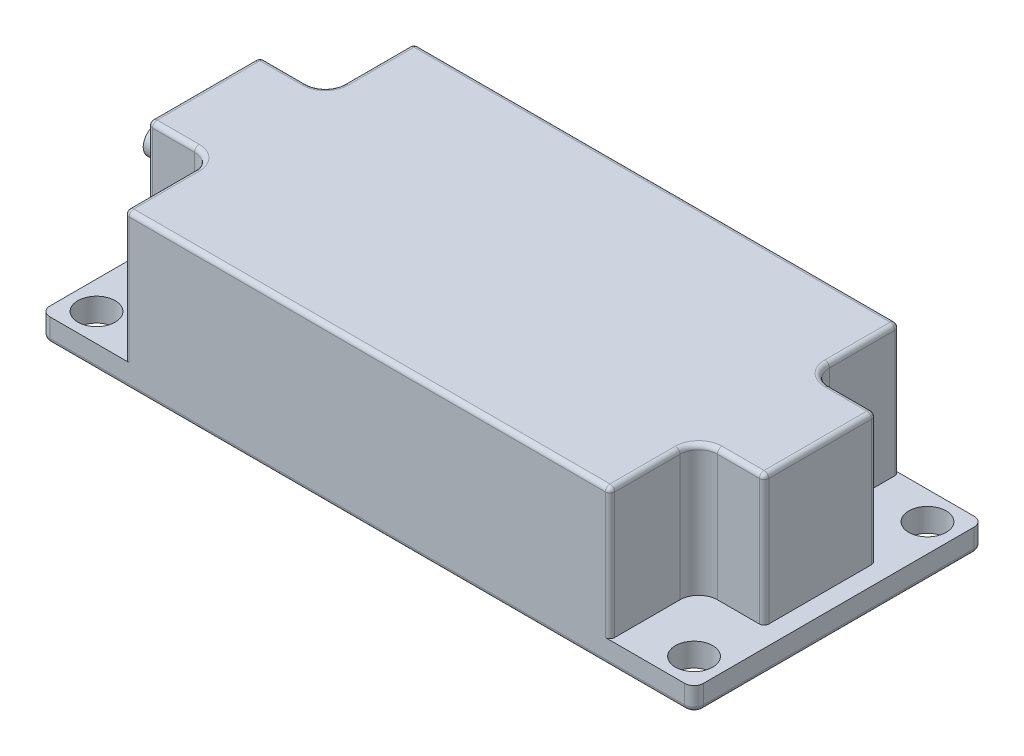
SolidWorks part; units mm, degrees
ref_plane "前视基准面" through (0, 0, 0) normal (0, 0, 1) x (1, 0, 0)
ref_plane "上视基准面" through (0, 0, 0) normal (0, 1, 0) x (1, 0, 0)
ref_plane "右视基准面" through (0, 0, 0) normal (1, 0, 0) x (0, 0, -1)
other "Configuration Table"
sketch "草图1" plane through (0, 0, 0) normal (0, 1, 0) x (1, 0, 0)
  line L0 (35, 0) -> (35, -31) construction
  line L1 (1, 0) -> (69, 0)
  line L2 (0, -1) -> (0, -30)
  line L3 (1, -31) -> (69, -31)
  line L4 (70, -1) -> (70, -30)
  line L5 (0, -15.5) -> (70, -15.5) construction
  circle A0 centre (3, -3) radius 2
  circle A4 centre (67, -3) radius 2
  circle A5 centre (67, -28) radius 2
  circle A6 centre (3, -28) radius 2
  arc A7 (69, 0) -> (70, -1) centre (69, -1) cw
  arc A8 (69, -31) -> (70, -30) centre (69, -30) ccw
  arc A9 (0, -30) -> (1, -31) centre (1, -30) ccw
  arc A10 (1, 0) -> (0, -1) centre (1, -1) ccw
  point P19 (70, 0)
  point P24 (0, -31)
  point P27 (0, 0)
  dimension "D3" = 4
  dimension "D4" = 12.5
  dimension "D5" = 32
  dimension "D6" = 1
  dimension "D1" = 70
  dimension "D2" = 31
extrude "凸台-拉伸1" add sketch "草图1" along normal blind 2.5
sketch "草图2" plane through (0, 2.5, 0) normal (0, 1, 0) x (1, 0, 0)
  line L0 (69, 0) -> (1, 0) construction
  line L1 (9, 0) -> (61, 0)
  line L2 (9, 0) -> (9, -31)
  line L3 (9, -31) -> (61, -31)
  line L4 (61, 0) -> (61, -31)
  line L5 (1, -31) -> (69, -31) construction
  line L6 (0, -15.5) -> (70, -15.5) construction
  line L7 (0, -1) -> (0, -30) construction
  line L8 (70, -30) -> (70, -1) construction
  line L9 (35, 0) -> (35, -31) construction
  line L10 (0, -9.5) -> (0, -21.5)
  line L11 (61, -9.5) -> (70, -9.5)
  line L12 (61, -9.5) -> (61, -21.5)
  line L13 (61, -21.5) -> (70, -21.5)
  line L14 (70, -9.5) -> (70, -21.5)
  line L15 (9, -21.5) -> (0, -21.5)
  line L16 (9, -9.5) -> (0, -9.5)
  line L17 (68, -9.5) -> (68, -21.5)
  line L18 (2, -9.5) -> (2, -21.5)
  line M12 (69, 0) -> (1, 0)
  line M16 (1, -31) -> (69, -31)
  dimension "D1" = 26
  dimension "D2" = 26
  dimension "D3" = 26
  dimension "D4" = 31
  dimension "D5" = 26
  dimension "D6" = 9
  dimension "D7" = 6
  dimension "D8" = 6
  dimension "D9" = 2
  dimension "D10" = 2
extrude "凸台-拉伸2" add sketch "草图2" along normal blind 14 contours L4 L2 M12 M16 | L16 L18 L15 L2 | L17 L11 L4 L13
fillet "圆角1" radius 2 1 edges at (9, 9.5, 21.5)
fillet "圆角2" radius 2 3 edges at (61, 9.5, 9.5) (9, 9.5, 9.5) (61, 9.5, 21.5)
fillet "圆角3" radius 0.5 32 edges at (69.7071, 0, 30.7071) (35, 0, 31) (0.2929, 0, 30.7071) (0, 0, 15.5) (0.2929, 0, 0.2929) (35, 0, 0) (69.7071, 0, 0.2929) (4.5, 16.5, 21.5) (2, 16.5, 15.5) (4.5, 16.5, 9.5) (8.4142, 16.5, 8.9142) (9, 16.5, 3.75) (35, 16.5, 31) (61, 16.5, 27.25) (61.5858, 16.5, 8.9142) (65.5, 16.5, 9.5) (68, 16.5, 15.5) (65.5, 16.5, 21.5) (61.5858, 16.5, 22.0858) (61, 16.5, 3.75) (35, 16.5, 0) (9, 16.5, 27.25) (8.4142, 16.5, 22.0858) (61, 9.5, 0) (9, 9.5, 0) (9, 9.5, 31) (2, 9.5, 21.5) (2, 9.5, 9.5) (61, 9.5, 31) (68, 9.5, 9.5) (68, 9.5, 21.5) (70, 0, 15.5)
sketch "草图3" plane through (0, 0, 0) normal (0, -1, 0) x (1, 0, 0)
  line L0 (0.5, 15.5) -> (69.5, 15.5) construction
  line L1 (0.5, 30) -> (0.5, 1) construction
  line L2 (69.5, 1) -> (69.5, 30) construction
  line L3 (16.2908, 15.5) -> (32.1875, 15.5) construction
  line L4 (16.2908, 25.0135) -> (32.1875, 25.0135)
  line L5 (16.2908, 5.9865) -> (32.1875, 5.9865)
  arc A0 (16.2908, 25.0135) -> (16.2908, 5.9865) centre (16.2908, 15.5) ccw
  arc A1 (32.1875, 5.9865) -> (32.1875, 25.0135) centre (32.1875, 15.5) ccw
  point P8 (24.2392, 15.5)
extrude "切除-拉伸1" cut sketch "草图3" against normal blind 0.5
sketch "草图4" plane through (2, 0, 0) normal (-1, 0, 0) x (0, 0, 1)
  line L0 (15.5, 16) -> (15.5, 2.5) construction
  line L1 (21, 16) -> (10, 16) construction
  line L2 (1, 2.5) -> (30, 2.5) construction
  circle A0 centre (15.5, 9.25) radius 1.5
  dimension "D1" = 3
extrude "凸台-拉伸3" add sketch "草图4" along normal blind 5
sketch "草图5" plane through (2, 0, 0) normal (-1, 0, 0) x (0, 0, 1)
  circle A0 centre (15.5, 9.25) radius 2.5
  dimension "D1" = 5
extrude "凸台-拉伸4" add sketch "草图5" along normal blind 1
